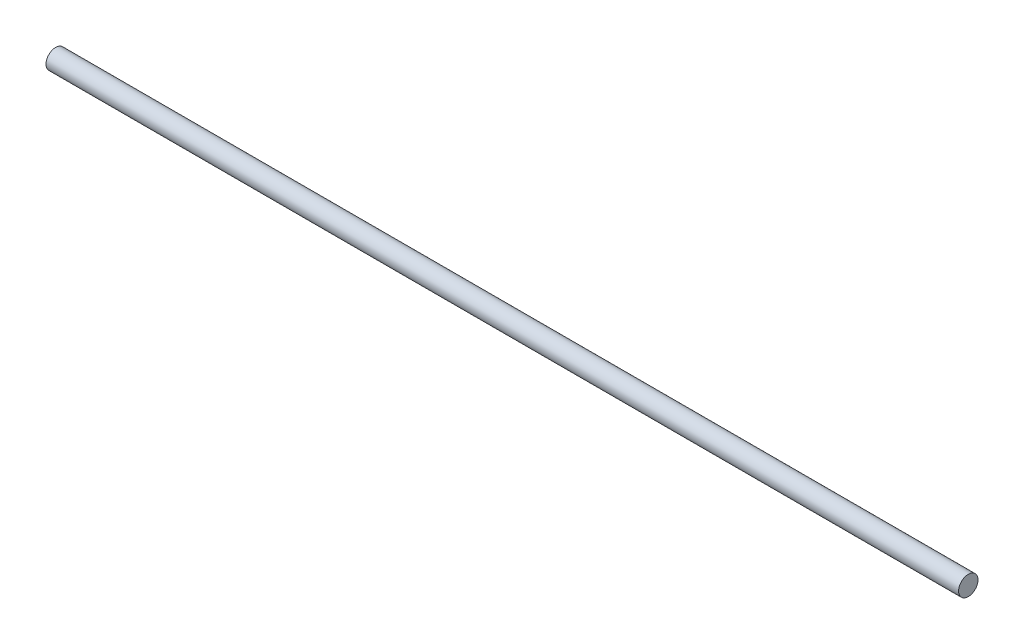
SolidWorks part; units mm, degrees
ref_plane "Front Plane" through (0, 0, 0) normal (0, 0, 1) x (1, 0, 0)
ref_plane "Top Plane" through (0, 0, 0) normal (0, 1, 0) x (1, 0, 0)
ref_plane "Right Plane" through (0, 0, 0) normal (1, 0, 0) x (0, 0, -1)
sketch "Sketch1" plane through (0, 0, 0) normal (1, 0, 0) x (0, 0, -1)
  circle A0 centre (0, 0) radius 6.35
  dimension "D1" = 12.7
extrude "Boss-Extrude1" add sketch "Sketch1" along normal blind 596.9
